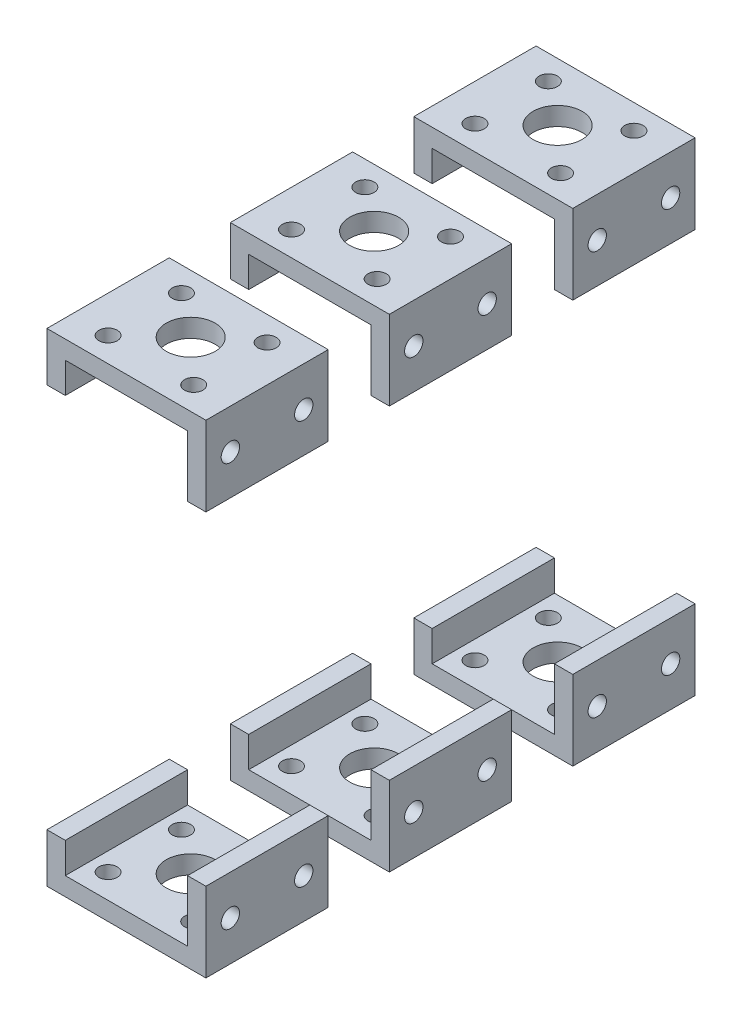
SolidWorks part; units mm, degrees
ref_plane "前视基准面" through (0, 0, 0) normal (0, 0, 1) x (1, 0, 0)
ref_plane "上视基准面" through (0, 0, 0) normal (0, 1, 0) x (1, 0, 0)
ref_plane "右视基准面" through (0, 0, 0) normal (1, 0, 0) x (0, 0, -1)
other "Configuration Table"
sketch "草图1" plane through (0, 0, 0) normal (0, 0, 1) x (1, 0, 0)
  line L9 (-8.64, -35.5) -> (-8.64, -39.5)
  line L10 (17.36, 39.5) -> (-8.64, 39.5)
  line L15 (55, 0) -> (-55, 0) construction
  line L22 (17.36, 39.5) -> (17.36, -39.5)
  line L23 (17.36, -39.5) -> (-8.64, -39.5)
  line L24 (-8.64, 39.5) -> (-8.64, 35.5)
  line L25 (14.36, 36.5) -> (-5.64, 36.5)
  line L26 (14.36, 36.5) -> (14.36, -36.5)
  line L27 (14.36, -36.5) -> (-5.64, -36.5)
  line L28 (-8.64, 35.5) -> (-8.64, 31.5)
  line L29 (-8.64, 31.5) -> (-5.64, 31.5)
  line L30 (-5.64, 36.5) -> (-5.64, 31.5)
  line L31 (-8.64, -31.5) -> (-5.64, -31.5)
  line L32 (-5.64, -36.5) -> (-5.64, -31.5)
  line L34 (-8.64, -35.5) -> (-8.64, -31.5)
  point P0 (0, 0)
  point P7 (0, 0)
  dimension "D1" = 79
  dimension "D2" = 3
  dimension "D3" = 3
  dimension "D4" = 3
  dimension "D5" = 26
  dimension "D6" = 63
  dimension "D7" = 3
extrude "凸台-拉伸1" add sketch "草图1" along normal blind 160
sketch "草图4" plane through (14.36, 0, 0) normal (-1, 0, 0) x (0, 0, 1)
  line L0 (160, -31.5) -> (0, -31.5) construction
  line L1 (140, 26.5) -> (160, 26.5)
  line L3 (140, -26.5) -> (160, -26.5)
  line L4 (160, 26.5) -> (160, -26.5)
  line L5 (140, 26.5) -> (160, -26.5) construction
  line L6 (140, -26.5) -> (160, 26.5) construction
  line L7 (160, 36.5) -> (160, -36.5) construction
  line L12 (140, 26.5) -> (140, 45.304)
  line L13 (100, -45.304) -> (110, -45.304)
  line L14 (110, -45.304) -> (110, -26.5)
  line L15 (110, -26.5) -> (130, -26.5)
  line L16 (130, -45.304) -> (140, -45.304)
  line L17 (140, -45.304) -> (140, -26.5)
  line L18 (140, 45.304) -> (130, 45.304)
  line L19 (130, 45.304) -> (130, 26.5)
  line L21 (110, 26.5) -> (130, 26.5)
  line L22 (110, 26.5) -> (110, 45.304)
  line L23 (110, 45.304) -> (100, 45.304)
  line L30 (100, 45.304) -> (100, 26.5)
  line L31 (72.3419, -45.304) -> (80, -45.304)
  line L34 (80, -45.304) -> (80, -26.5)
  line L35 (80, -26.5) -> (100, -26.5)
  line L39 (80, 26.5) -> (100, 26.5)
  line L42 (80, 26.5) -> (80, 45.304)
  line L43 (80, 45.304) -> (72.3419, 45.304)
  line L45 (100, -26.5) -> (100, -45.304)
  line L46 (130, -26.5) -> (130, -45.304)
  line L47 (72.3419, 45.304) -> (72.3419, 47.203)
  line L48 (-21.5766, -47.2023) -> (72.3419, -47.2023)
  line L49 (72.3419, -47.2023) -> (72.3419, -45.304)
  line L50 (72.3419, 47.203) -> (-21.5766, 47.203)
  line L51 (-21.5766, 47.203) -> (-21.5766, -47.2023)
  line L66 (100, 26.5) -> (100, -26.5) [skipped]
  line L67 (130, 26.5) -> (130, -26.5) [skipped]
  line L68 (70, 45.304) -> (70, -45.304) [skipped]
  point P10 (150, 0)
  dimension "D1" = 53
  dimension "D2" = 5
  dimension "D3" = 10
  dimension "D4" = 20
extrude "切除-拉伸2" cut sketch "草图4" against normal through all and the other way through all
sketch "草图5" plane through (17.36, 0, 0) normal (1, 0, 0) x (0, 0, -1)
  line L0 (-80, -26.5) -> (-100, -26.5) construction
  line L1 (-100, -26.5) -> (-100, -39.5) construction
  line L2 (-80, -39.5) -> (-80, -26.5) construction
  line L3 (-103.1277, -33) -> (-76.998, -33) construction
  line L4 (-100, -39.5) -> (-80, -39.5) construction
  line L5 (14.3, 0) -> (-14.3, 0) construction
  circle A0 centre (-96, -33) radius 1.5
  circle A1 centre (-84, -33) radius 1.5
  circle A24 centre (-126, -33) radius 1.5
  circle A26 centre (-114, -33) radius 1.5
  circle A28 centre (-156, -33) radius 1.5
  circle A30 centre (-144, -33) radius 1.5
  circle A34 centre (-84, 33) radius 1.5
  circle A35 centre (-96, 33) radius 1.5
  circle A37 centre (-114, 33) radius 1.5
  circle A39 centre (-126, 33) radius 1.5
  circle A41 centre (-144, 33) radius 1.5
  circle A43 centre (-156, 33) radius 1.5
  dimension "D1" = 6.5
  dimension "D3" = 4
  dimension "D2" = 4
  dimension "D4" = 3
  dimension "D6" = 6.5
  dimension "D7" = 6.5
extrude "切除-拉伸3" cut sketch "草图5" against normal up to next (3 mm away)
sketch "草图6" plane through (0, -39.5, 0) normal (0, -1, 0) x (1, 0, 0)
  line L0 (17.36, 100) -> (-8.64, 100) construction
  line L1 (-8.64, 80) -> (17.36, 80) construction
  line L2 (17.36, 100) -> (17.36, 80) construction
  line L3 (4.36, 100) -> (4.36, 78.9718) construction
  circle A0 centre (11.36, 96) radius 1.5
  circle A1 centre (11.36, 84) radius 1.5
  circle A2 centre (-2.64, 84) radius 1.5
  circle A3 centre (-2.64, 96) radius 1.5
  circle A4 centre (-2.64, 126) radius 1.5
  circle A5 centre (-2.64, 114) radius 1.5
  circle A6 centre (11.36, 114) radius 1.5
  circle A7 centre (11.36, 126) radius 1.5
  circle A8 centre (-2.64, 156) radius 1.5
  circle A9 centre (-2.64, 144) radius 1.5
  circle A10 centre (11.36, 144) radius 1.5
  circle A11 centre (11.36, 156) radius 1.5
  circle A12 centre (4.36, 89.4859) radius 4
  circle A13 centre (4.36, 119.4859) radius 4
  circle A14 centre (4.36, 149.4859) radius 4
  dimension "D1" = 4
  dimension "D6" = 3
  dimension "D2" = 4
  dimension "D3" = 6
  dimension "D4" = 6
  dimension "D5" = 3
extrude "切除-拉伸4" cut sketch "草图6" against normal up to next (3 mm away)
mirror "镜向1" about plane through (0, 0, 0) normal (0, 1, 0) of "切除-拉伸4"
equation "\"7。5\"=6.5"
